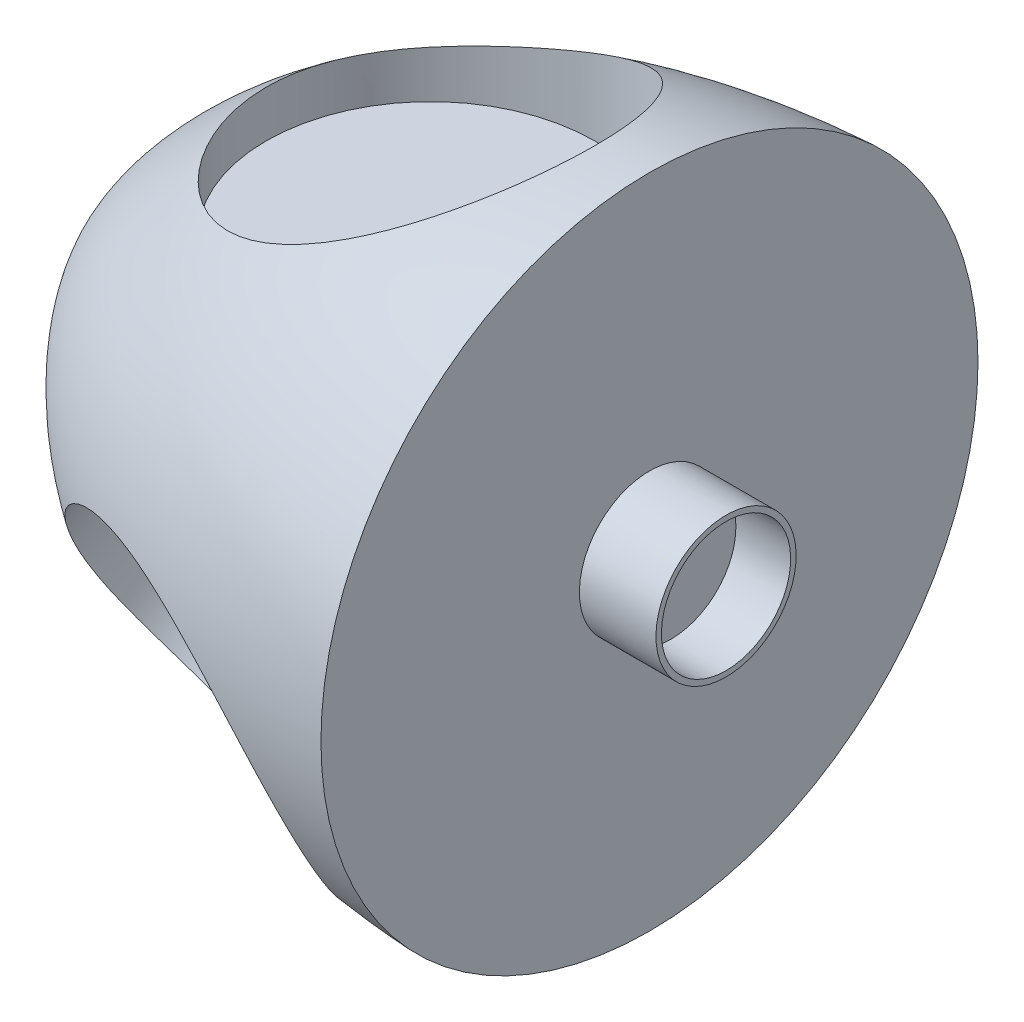
SolidWorks part; units mm, degrees
ref_plane "Front Plane" through (0, 0, 0) normal (0, 0, 1) x (1, 0, 0)
ref_plane "Top Plane" through (0, 0, 0) normal (0, 1, 0) x (1, 0, 0)
ref_plane "Right Plane" through (0, 0, 0) normal (1, 0, 0) x (0, 0, -1)
sketch "Sketch1" plane through (0, 0, 0) normal (0, 0, 1) x (1, 0, 0)
  line L0 (0, 0) -> (-5000, 0)
  line L1 (0, 0) -> (0, 3000)
  spline S0 degree 3 poles (0, 3000) (-1941.2327, 2903.0795) (-4138.1255, 2194.7274) (-5000, 0) knots 0 0 0 0 1 1 1 1
revolve "Revolve1" add sketch "Sketch1" angle 360 about L0
ref_plane "Plane1" through (0, 3000, 0) normal (0, 1, 0) x (1, 0, 0)
sketch "Sketch2" plane through (0, 3000, 0) normal (0, 1, 0) x (1, 0, 0)
  line L0 (-2000, 0) -> (0, 0) construction
  circle A0 centre (-2000, 0) radius 1500
extrude "Cut-Extrude1" cut sketch "Sketch2" against normal blind 1500
pattern_circular "CirPattern1" count 3 over 360 about axis through (0, 0, 0) along (1, 0, 0) of "Cut-Extrude1"
sketch "Sketch3" plane through (0, 0, 0) normal (1, 0, 0) x (0, 0, -1)
  circle A0 centre (0, 0) radius 1000
sketch "Sketch4" plane through (0, 0, 0) normal (1, 0, 0) x (0, 0, -1)
  point P0 (0, 0)
ref_plane "Plane3" through (0, 0, 0) normal (0, -0.866, -0.5) x (-1, 0, 0)
sketch "Sketch5" plane through (0, 0, 0) normal (0, -0.866, -0.5) x (-1, 0, 0)
  line L0 (0, 0) -> (-779.5092, 0) construction
  line L1 (0, 0) -> (0, 640)
  line L2 (0, 640) -> (-699.2667, 640)
  line L3 (-699.2667, 640) -> (-699.2667, 590)
  line L4 (-699.2667, 590) -> (-199.2667, 590)
  line L5 (-199.2667, 590) -> (-199.2667, 0)
  line L12 (-199.2667, 0) -> (0, 0)
  point P8 (-199.2667, 0)
  point P9 (-238.8188, 0)
revolve "Revolve2" add sketch "Sketch5" angle 360 about L0
